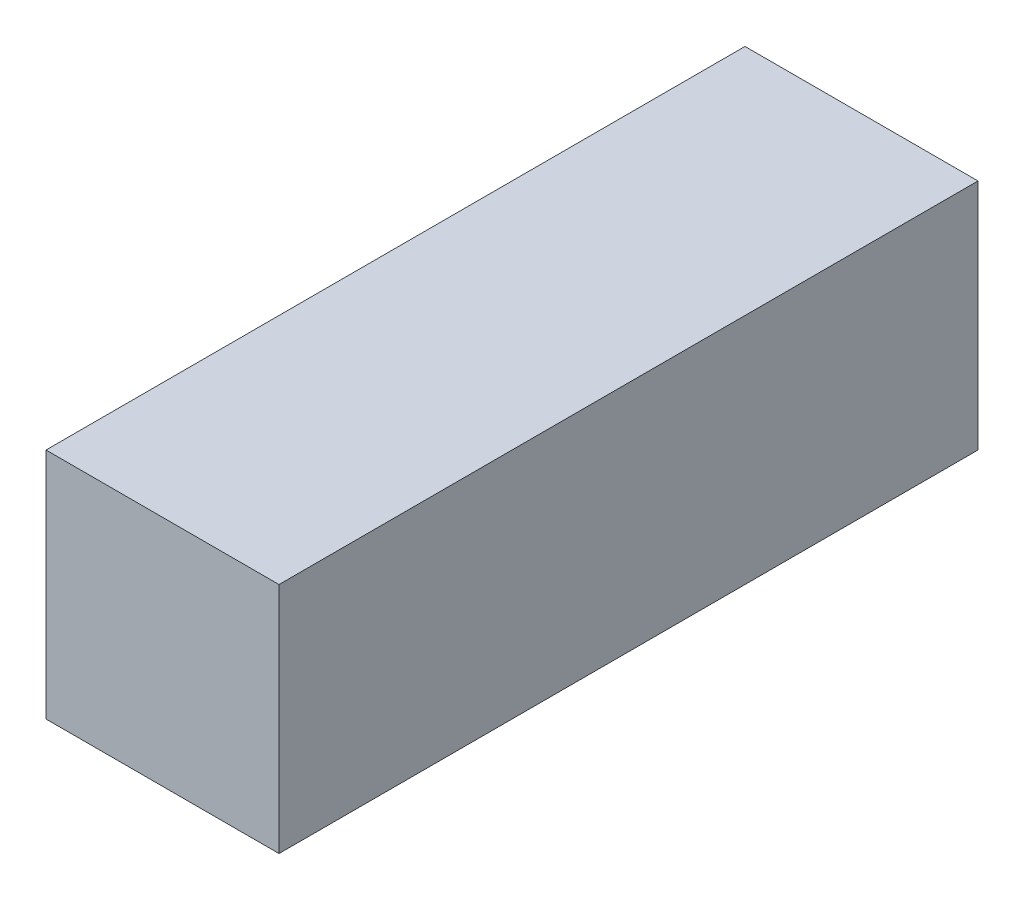
SolidWorks part; units mm, degrees
ref_plane "Front Plane" through (0, 0, 0) normal (0, 0, 1) x (1, 0, 0)
ref_plane "Top Plane" through (0, 0, 0) normal (0, 1, 0) x (1, 0, 0)
ref_plane "Right Plane" through (0, 0, 0) normal (1, 0, 0) x (0, 0, -1)
sketch "Sketch1" plane through (0, 0, 0) normal (0, 0, 1) x (1, 0, 0)
  line L1 (0, 0) -> (5, 0)
  line L2 (0, 0) -> (0, 5)
  line L3 (0, 5) -> (5, 5)
  line L4 (5, 0) -> (5, 5)
  dimension "D1" = 5
  dimension "D2" = 5
extrude "Boss-Extrude1" add sketch "Sketch1" along normal blind 15
